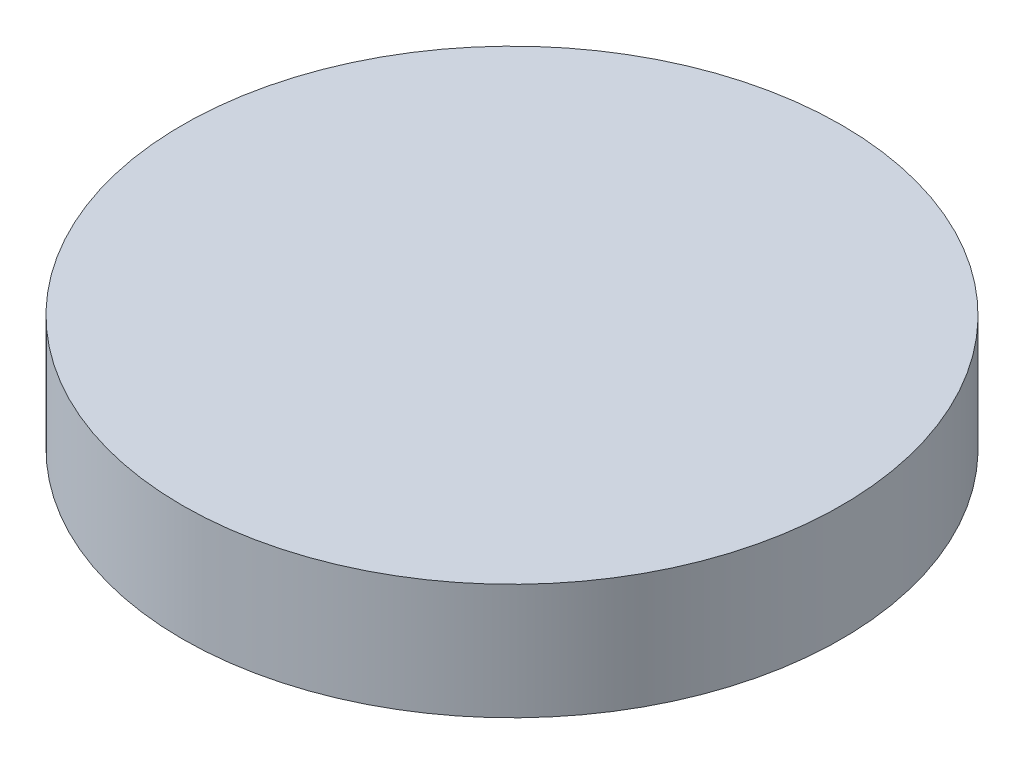
SolidWorks part; units mm, degrees
ref_plane "前视基准面" through (0, 0, 0) normal (0, 0, 1) x (1, 0, 0)
ref_plane "上视基准面" through (0, 0, 0) normal (0, 1, 0) x (1, 0, 0)
ref_plane "右视基准面" through (0, 0, 0) normal (1, 0, 0) x (0, 0, -1)
sketch "草图1" plane through (0, 0, 0) normal (0, 1, 0) x (1, 0, 0)
  circle A0 centre (0, 0) radius 28.5
  dimension "D1" = 57
extrude "凸台-拉伸1" add sketch "草图1" along normal blind 10
